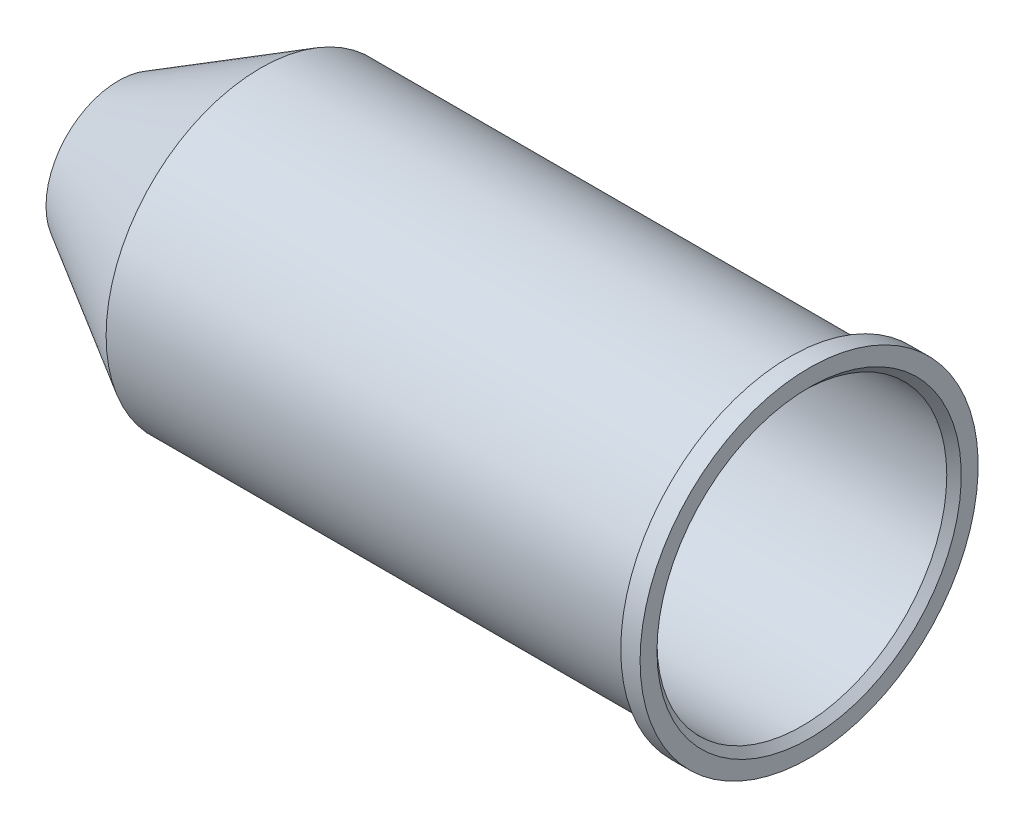
SolidWorks part; units mm, degrees
ref_plane "Спереди" through (0, 0, 0) normal (0, 0, 1) x (1, 0, 0)
ref_plane "Сверху" through (0, 0, 0) normal (0, 1, 0) x (1, 0, 0)
ref_plane "Справа" through (0, 0, 0) normal (1, 0, 0) x (0, 0, -1)
sketch "Эскиз1" plane through (0, 0, 0) normal (0, 0, 1) x (1, 0, 0)
  line L0 (0, 0) -> (143, 0) construction
  line L1 (0, 15) -> (29.4449, 32)
  line L2 (29.4449, 32) -> (139, 32)
  line L3 (139, 32) -> (139, 35)
  line L4 (139, 35) -> (143, 35)
  line L5 (143, 35) -> (143, 31.5)
  line L6 (141.5, 30) -> (41.5, 30)
  line L7 (41.5, 30) -> (19.3942, 7.8942)
  line L8 (0, 15) -> (0, 12)
  line L9 (0, 12) -> (16.7942, 7.5)
  line L12 (143, 31.5) -> (141.5, 30)
  line L13 (16.9486, 7.4651) -> (17.6168, 7.3417)
  arc A3 (19.3942, 7.8942) -> (17.6168, 7.3417) centre (17.98, 9.3084) cw
  arc A4 (16.7942, 7.5) -> (16.9486, 7.4651) centre (17.3119, 9.4319) ccw
  point P9 (143, 30)
  point P15 (18.7741, 7.3885)
  point P18 (18.0225, 7.5624)
  point P21 (18.8935, 7.6651)
  point P22 (17.6733, 7.5)
  point P23 (18.8422, 7.6593)
  point P24 (16.7942, 7.5)
  point P25 (17.981, 7.466)
  point P26 (19.7334, 8.2334)
  point P27 (18.7415, 7.466)
  point P28 (18.7717, 7.5435)
  point P29 (18.1834, 7.4327)
  dimension "D13" = 2
  dimension "D14" = 2
  dimension "D15" = 2.6
  dimension "D1" = 143
  dimension "D2" = 60
  dimension "D3" = 64
  dimension "D4" = 70
  dimension "D5" = 4
  dimension "D6" = 30
  dimension "D7" = 45
  dimension "D8" = 30
  dimension "D9" = 24
  dimension "D10" = 15
  dimension "D11" = 101.5
  dimension "D12" = 15
revolve "Повернуть1" add sketch "Эскиз1" angle 360 about L0
